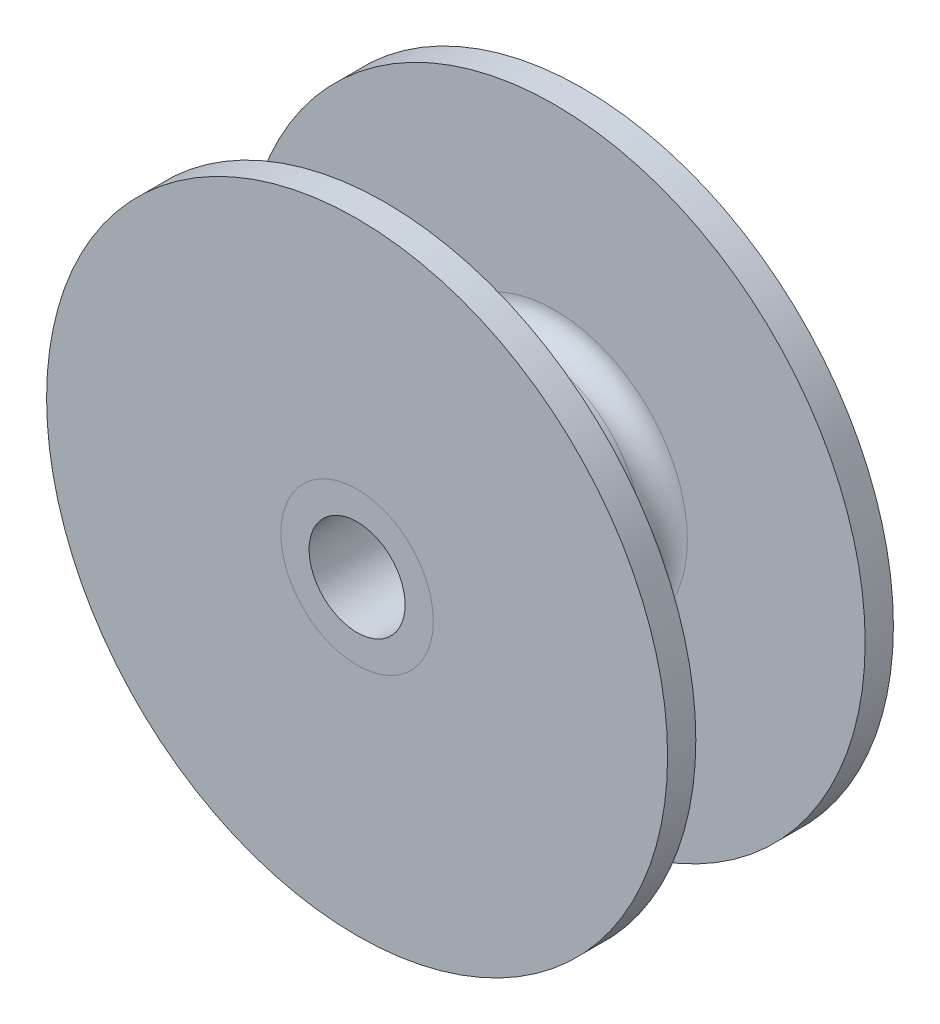
SolidWorks part; units mm, degrees
material "Gray Cast Iron"
ref_plane "Front Plane" through (0, 0, 0) normal (0, 0, 1) x (1, 0, 0)
ref_plane "Top Plane" through (0, 0, 0) normal (0, 1, 0) x (1, 0, 0)
ref_plane "Right Plane" through (0, 0, 0) normal (1, 0, 0) x (0, 0, -1)
sketch "Sketch2" plane through (0, 0, 0) normal (1, 0, 0) x (0, 0, -1)
  line L1 (0, 0) -> (80, 0)
  line L2 (0, 0) -> (0, 110)
  line L3 (0, 110) -> (80, 110)
  line L4 (80, 0) -> (80, 110)
  dimension "D1" = 110
  dimension "D2" = 80
revolve "Revolve1" add sketch "Sketch2" angle 360 about L1
sketch "Sketch3" plane through (0, 0, 0) normal (1, 0, 0) x (0, 0, -1)
  line L0 (-1000, 0) -> (49000, 0) construction
  line L1 (0, 110) -> (0, -110) construction
  line L2 (80, 110) -> (0, 110) construction
  line L3 (10, 110) -> (10, 47)
  line L4 (18, 39) -> (62, 39)
  line L5 (70, 47) -> (70, 110)
  line L6 (80, -110) -> (80, 110) construction
  line L7 (10, 110) -> (70, 110)
  arc A0 (62, 39) -> (70, 47) centre (62, 47) ccw
  arc A1 (10, 47) -> (18, 39) centre (18, 47) ccw
  dimension "D4" = 8
  dimension "D1" = 10
  dimension "D2" = 10
  dimension "D3" = 39
sketch "Sketch6" plane through (0, 0, 0) normal (0, 0, 1) x (1, 0, 0)
  circle A0 centre (0, 0) radius 27
  dimension "D1" = 54
extrude "Cut-Extrude2" cut sketch "Sketch6" against normal through all
sketch "Sketch7" plane through (0, 0, 0) normal (0, 1, 0) x (1, 0, 0)
  line L0 (-1110, 40) -> (48890, 40) construction
  line L1 (-110, 80) -> (-110, 0) construction
  line L2 (0, -1000) -> (0, 49000) construction
  circle A0 centre (0, 40) radius 2
  point P5 (-110, 40)
  dimension "D1" = 4
extrude "Cut-Extrude3" cut sketch "Sketch7" against normal through all both and the other way through all
revolve "Cut-Revolve1" cut sketch "Sketch3" angle 360 about L0
sketch "Sketch8" plane through (0, 0, 0) normal (0, 0, 1) x (1, 0, 0)
  circle A0 centre (0, 0) radius 27
  circle A1 centre (0, 0) radius 27 construction
  circle A2 centre (0, 0) radius 17
  dimension "D1" = 34
extrude "Boss-Extrude1" add sketch "Sketch8" against normal blind 25 separate body
ref_plane "Plane1" through (0, 0, -40) normal (0, 0, 1) x (1, 0, 0)
mirror "Mirror2" about plane through (0, 0, -40) normal (0, 0, 1) of bodies 110
